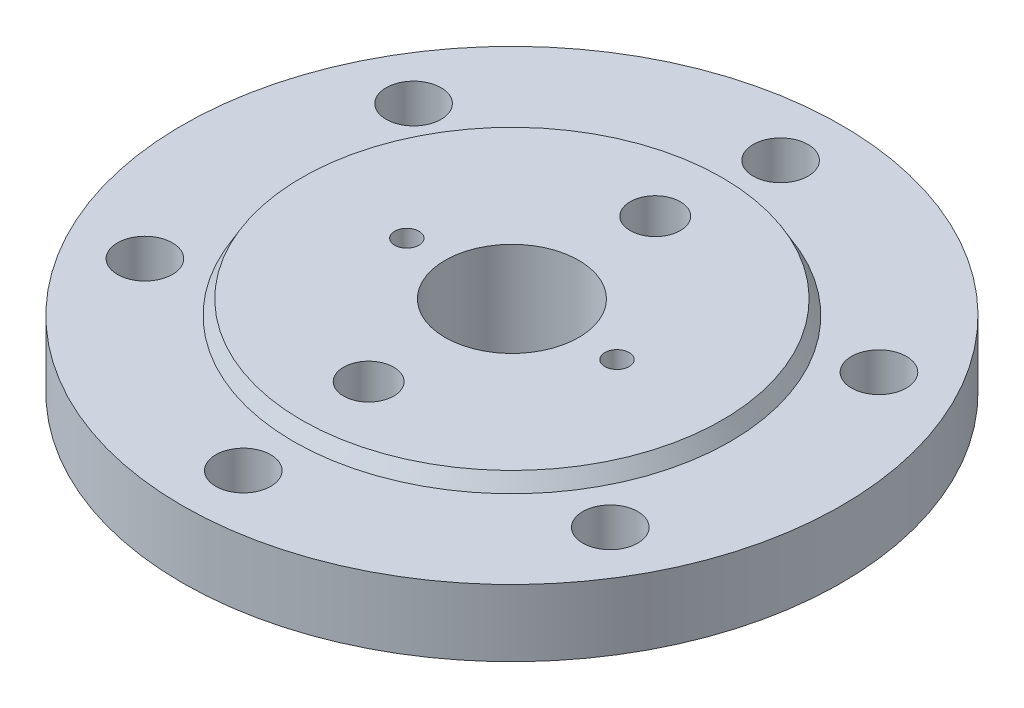
SolidWorks part; units mm, degrees
ref_plane "Front Plane" through (0, 0, 0) normal (0, 0, 1) x (1, 0, 0)
ref_plane "Top Plane" through (0, 0, 0) normal (0, 1, 0) x (1, 0, 0)
ref_plane "Right Plane" through (0, 0, 0) normal (1, 0, 0) x (0, 0, -1)
sketch "Sketch1" plane through (0, 0, 0) normal (0, 0, 1) x (1, 0, 0)
  line L0 (0, 62.9923) -> (0, -42.2928) construction
  line L7 (14, -37.7714) -> (14, -8.7049)
  line L8 (14, -8.7049) -> (28, -0.622)
  line L9 (28, -0.622) -> (28, 49.2286)
  line L10 (28, 49.2286) -> (88, 49.2286)
  line L11 (88, 49.2286) -> (91.4641, 43.2286)
  line L12 (91.4641, 43.2286) -> (138, 43.2286)
  line L13 (138, 43.2286) -> (138, 15.2286)
  line L14 (138, 15.2286) -> (59.9018, 15.2286)
  line L15 (59.9018, 15.2286) -> (59.9018, 9.2286)
  line L16 (59.9018, 9.2286) -> (35, -37.7714)
  line L17 (35, -37.7714) -> (14, -37.7714)
  dimension "D1" = 28
  dimension "D2" = 87
  dimension "D3" = 35
  dimension "D4" = 14
  dimension "D5" = 28
  dimension "D6" = 60
  dimension "D9" = 6
  dimension "D10" = 6
  dimension "D11" = 47
revolve "Revolve1" add sketch "Sketch1" angle 360 about L0
sketch "Sketch2" plane through (0, 43.2286, 0) normal (0, 1, 0) x (1, 0, 0)
  line L0 (0, 0) -> (0, 114.1114) construction
  line L1 (0, 0) -> (119.0281, 0) construction
  circle A0 centre (0, 112.5) radius 11.5
  circle A1 centre (97.4279, 56.25) radius 11.5
  circle A2 centre (97.4279, -56.25) radius 11.5
  circle A3 centre (0, -112.5) radius 11.5
  circle A4 centre (-97.4279, -56.25) radius 11.5
  circle A5 centre (-97.4279, 56.25) radius 11.5
  point P19 (0, 0)
  dimension "D2" = 23
  dimension "D1" = 112.5
  dimension "D3" = 6
extrude "Cut-Extrude1" cut sketch "Sketch2" against normal up to next
sketch "Sketch7" plane through (0, 49.2286, 0) normal (0, 1, 0) x (1, 0, 0)
  line L0 (0, 60) -> (0, -60)
  dimension "D1" = 120
hole_wizard "M24 Tapped Hole1" positions "3DSketch2" profile "Sketch8" tap size "M24" standard "ISO"
sketch3d "3DSketch2"
  point P0 (0, 49.2286, -60)
  point P3 (0, 49.2286, 60)
sketch "Sketch8" plane through (0, 49.2286, -60) normal (1, 0, 0) x (0, 0, 1)
  line L0 (0, 0) -> (0, 24)
  line L1 (0, 24) -> (10.5, 17.691)
  line L2 (10.5, 17.691) -> (10.5, 0)
  line L5 (10.5, 0) -> (0, 0)
  line L10 (0, 24) -> (-10.5, 17.691) construction
  line L11 (0, -6.35) -> (0, 107.95) construction
  dimension "Tap Drill Dia." = 21
  dimension "Tap Drill Depth" = 24
  dimension "Drill Angle" = 118
cosmetic thread "Hole Thread1" parameters "D1"=21, "D2"=24
cosmetic thread "Hole Thread2" parameters "D1"=21, "D2"=24
sketch "Sketch9" plane through (0, 49.2286, 0) normal (0, 1, 0) x (1, 0, 0)
  line L0 (-44, 0) -> (44, 0)
  dimension "D1" = 88
hole_wizard "M12 Tapped Hole1" positions "3DSketch3" profile "Sketch10" tap size "M12" standard "ISO"
sketch3d "3DSketch3"
  point P0 (-44, 49.2286, 0)
  point P3 (44, 49.2286, 0)
sketch "Sketch10" plane through (-44, 49.2286, 0) normal (1, 0, 0) x (0, 0, 1)
  line L0 (0, 0) -> (0, 12)
  line L1 (0, 12) -> (5.1, 8.9356)
  line L2 (5.1, 8.9356) -> (5.1, 0)
  line L5 (5.1, 0) -> (0, 0)
  line L10 (0, 12) -> (-5.1, 8.9356) construction
  line L11 (0, -6.35) -> (0, 107.95) construction
  dimension "Tap Drill Dia." = 10.2
  dimension "Tap Drill Depth" = 12
  dimension "Drill Angle" = 118
cosmetic thread "Hole Thread3" parameters "D1"=12, "D2"=12
cosmetic thread "Hole Thread4" parameters "D1"=12, "D2"=12
